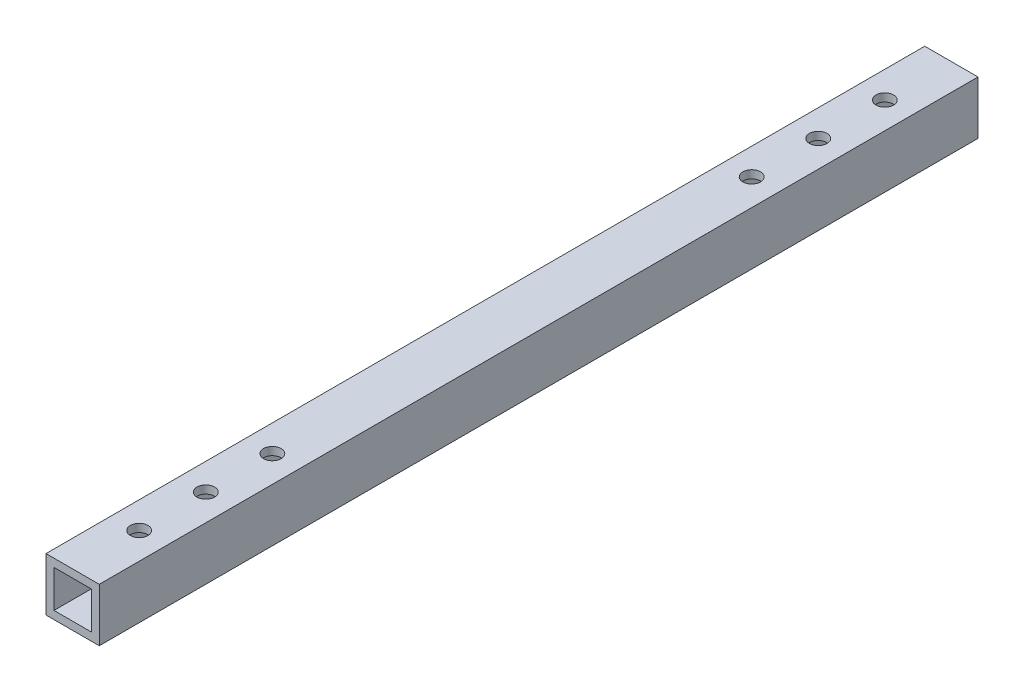
SolidWorks part; units mm, degrees
material "PC 高粘度"
ref_plane "前视基准面" through (0, 0, 0) normal (0, 0, 1) x (1, 0, 0)
ref_plane "上视基准面" through (0, 0, 0) normal (0, 1, 0) x (1, 0, 0)
ref_plane "右视基准面" through (0, 0, 0) normal (1, 0, 0) x (0, 0, -1)
other "Configuration Table"
sketch "草图1" plane through (0, 0, 0) normal (0, 0, 1) x (1, 0, 0)
  line L1 (-5, 5) -> (5, 5)
  line L2 (-5, 5) -> (-5, -5)
  line L3 (-5, -5) -> (5, -5)
  line L4 (5, 5) -> (5, -5)
  line L5 (-5, 5) -> (5, -5) construction
  line L6 (-5, -5) -> (5, 5) construction
  line L7 (-3.5, 3.5) -> (3.5, 3.5)
  line L8 (-3.5, 3.5) -> (-3.5, -3.5)
  line L9 (-3.5, -3.5) -> (3.5, -3.5)
  line L10 (3.5, 3.5) -> (3.5, -3.5)
  line L11 (-3.5, 3.5) -> (3.5, -3.5) construction
  line L12 (-3.5, -3.5) -> (3.5, 3.5) construction
  point P0 (0, 0)
  point P5 (0, 0)
  dimension "D1" = 10
  dimension "D2" = 1.5
  dimension "D3" = 10
extrude "凸台-拉伸1" add sketch "草图1" along normal blind 165
sketch "草图2" plane through (0, 5, 0) normal (0, 1, 0) x (1, 0, 0)
  circle A0 centre (0, -12.5) radius 1.65 construction
  circle A1 centre (0, -25) radius 1.65 construction
  circle A2 centre (0, -37.5) radius 1.65 construction
  circle A3 centre (0, -127.5) radius 1.65 construction
  circle A4 centre (0, -140) radius 1.65 construction
  circle A5 centre (0, -152.5) radius 1.65 construction
  circle A6 centre (0, -12.5) radius 1.65
  circle A7 centre (0, -25) radius 1.65
  circle A8 centre (0, -37.5) radius 1.65
  circle A9 centre (0, -127.5) radius 1.65
  circle A10 centre (0, -140) radius 1.65
  circle A11 centre (0, -152.5) radius 1.65
extrude "切除-拉伸1" cut sketch "草图2" against normal through all
